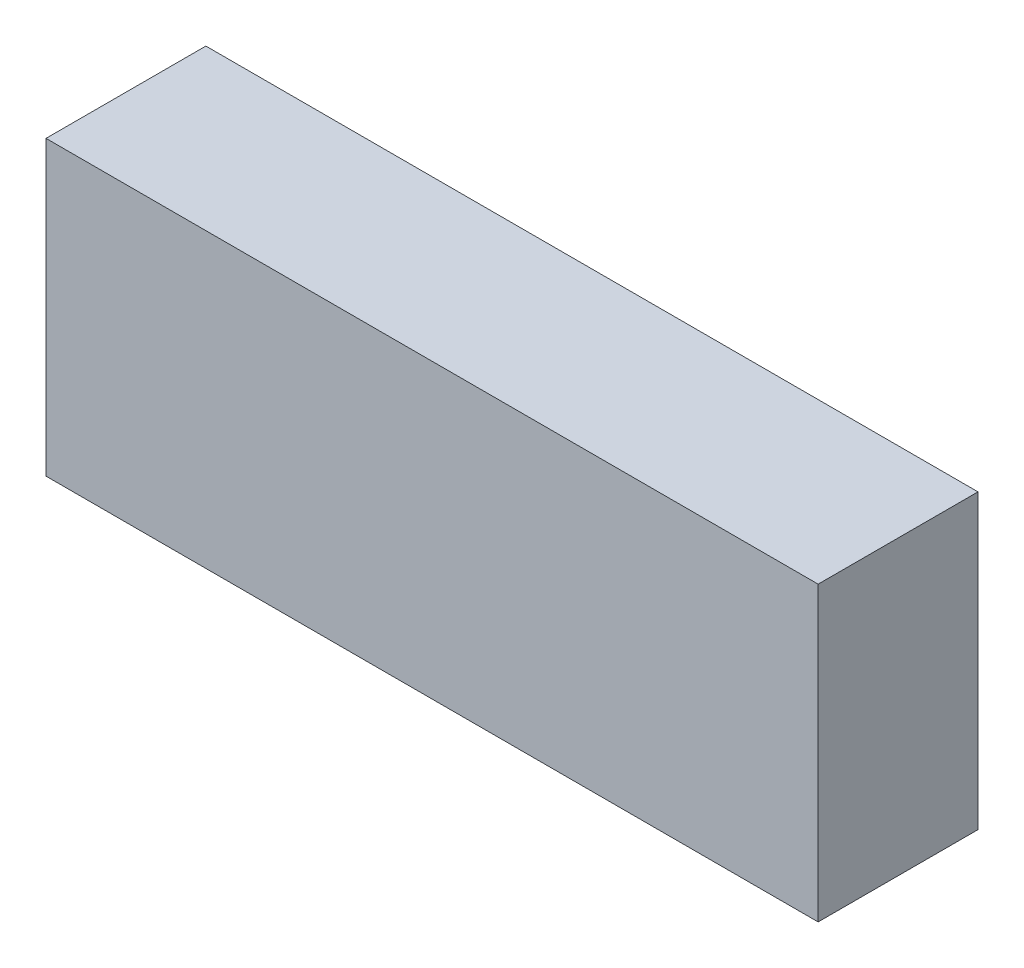
SolidWorks part; units mm, degrees
ref_plane "前视基准面" through (0, 0, 0) normal (0, 0, 1) x (1, 0, 0)
ref_plane "上视基准面" through (0, 0, 0) normal (0, 1, 0) x (1, 0, 0)
ref_plane "右视基准面" through (0, 0, 0) normal (1, 0, 0) x (0, 0, -1)
sketch "草图1" plane through (0, 0, 0) normal (0, 0, 1) x (1, 0, 0)
  line L0 (0, 0) -> (0, 18.3) construction
  line L3 (24.15, 18.3) -> (-24.15, 18.3)
  line L4 (24.15, 18.3) -> (24.15, 0)
  line L5 (24.15, 0) -> (-24.15, 0)
  line L6 (-24.15, 18.3) -> (-24.15, 0)
  line L7 (24.15, 18.3) -> (-24.15, 0) construction
  line L8 (24.15, 0) -> (-24.15, 18.3) construction
  point P5 (0, 9.15)
  point P10 (24.15, 18.3)
extrude "凸台-拉伸1" add sketch "草图1" along normal blind 10
